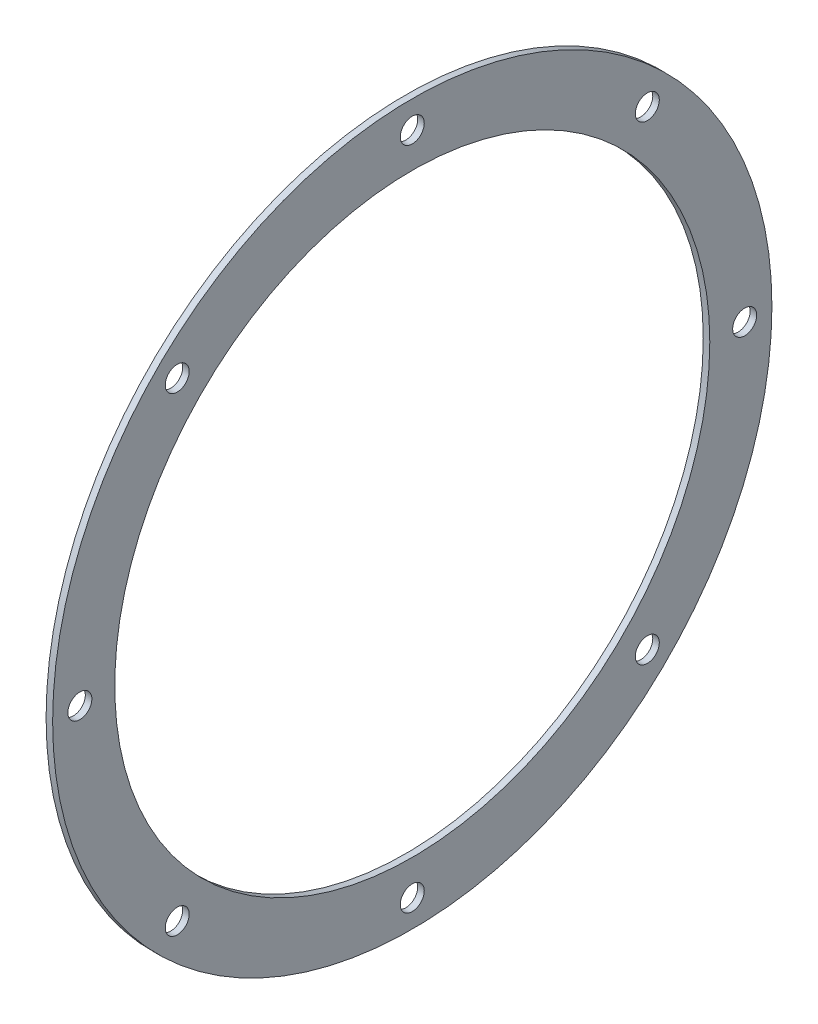
SolidWorks part; units mm, degrees
ref_plane "Vorderansicht" through (0, 0, 0) normal (0, 0, 1) x (1, 0, 0)
ref_plane "Draufsicht" through (0, 0, 0) normal (0, 1, 0) x (1, 0, 0)
ref_plane "Seitenansicht" through (0, 0, 0) normal (1, 0, 0) x (0, 0, -1)
sketch "Skizze2" plane through (0, 0, 0) normal (1, 0, 0) x (0, 0, -1)
  circle A1 centre (0, 0) radius 136.5
  circle A2 centre (0, 0) radius 165
  dimension "D1" = 330
  dimension "D2" = 273
extrude "Aufsatz-Linear austragen1" add sketch "Skizze2" against normal blind 3 separate body
hole_wizard "Durchgangsloch für M101" positions "Skizze5" profile "Skizze4" hole size "M10" standard "DIN" end condition up to next
sketch "Skizze5" plane through (0, -26.5034, -77.5866) normal (1, 0, 0) x (0, 0, -1)
  point P0 (-77.5866, 179.0034)
  dimension "D1" = 152.5
sketch "Skizze4" plane through (0, 152.5, 0) normal (0, 1, 0) x (0, 0, -1)
  line L0 (0, 0) -> (0, 3.001)
  line L1 (0, 3.001) -> (5.5, 3.001)
  line L2 (5.5, 3.001) -> (5.5, 0)
  line L5 (5.5, 0) -> (0, 0)
  line L11 (0, -6.35) -> (0, 107.95) construction
  dimension "Bohrerdurchmesser" = 11
  dimension "Bohrungstiefe" = 3.001
pattern_circular "Kreismuster1" count 8 over 360 about axis through (0, 0, 0) along (1, 0, 0) of "Durchgangsloch für M101"
